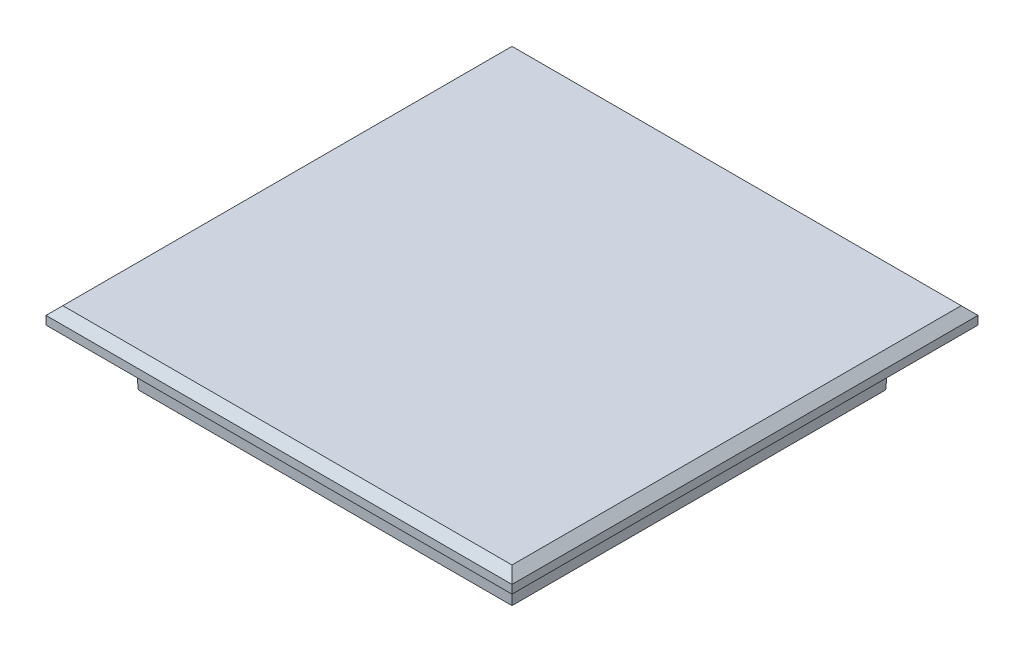
SolidWorks part; units mm, degrees
ref_plane "Front Plane" through (0, 0, 0) normal (0, 0, 1) x (1, 0, 0)
ref_plane "Top Plane" through (0, 0, 0) normal (0, 1, 0) x (1, 0, 0)
ref_plane "Right Plane" through (0, 0, 0) normal (1, 0, 0) x (0, 0, -1)
sketch "Sketch1" plane through (0, 0, 0) normal (0, 1, 0) x (1, 0, 0)
  line L0 (0, 43.1919) -> (0, -36.1744) construction
  line L1 (-68, 0) -> (63.8488, 0) construction
  line L3 (-34, -34) -> (34, -34) construction
  line L4 (-34, -34) -> (-34, 34) construction
  line L5 (-34, 34) -> (34, 34) construction
  line L6 (34, -34) -> (34, 34) construction
  line L7 (-34, -34) -> (34, 34) construction
  line L8 (-34, 34) -> (34, -34) construction
  line L12 (-33.8, 33.8) -> (33.8, 33.8)
  line L13 (33.8, -33.8) -> (33.8, 33.8)
  line L14 (-33.8, -33.8) -> (33.8, -33.8)
  line L15 (-33.8, -33.8) -> (-33.8, 33.8)
  line L16 (-30.8, 30.8) -> (30.8, 30.8)
  line L17 (30.8, -30.8) -> (30.8, 30.8)
  line L18 (-30.8, -30.8) -> (30.8, -30.8)
  line L19 (-30.8, -30.8) -> (-30.8, 30.8)
  point P5 (0, 0)
  dimension "D1" = 68
  dimension "D2" = 0.2
  dimension "D3" = 3
extrude "Boss-Extrude1" add sketch "Sketch1" against normal blind 10 draft 3
sketch "Sketch2" plane through (0, 0, 0) normal (0, 1, 0) x (1, 0, 0)
  line L1 (-41.5, -41.5) -> (41.5, -41.5)
  line L2 (-41.5, -41.5) -> (-41.5, 41.5)
  line L3 (-41.5, 41.5) -> (41.5, 41.5)
  line L4 (41.5, -41.5) -> (41.5, 41.5)
  line L5 (-41.5, -41.5) -> (41.5, 41.5) construction
  line L6 (-41.5, 41.5) -> (41.5, -41.5) construction
  point P0 (0, 0)
  dimension "D1" = 83
extrude "Boss-Extrude2" add sketch "Sketch2" along normal blind 3
chamfer "Chamfer1" distance 1.5 angle 45 4 edges at (0, 3, 41.5) (-41.5, 3, 0) (0, 3, -41.5) (41.5, 3, 0)
chamfer "Chamfer2" distance 2 angle 45 4 edges at (30.8, 0, 0) (0, 0, -30.8) (-30.8, 0, 0) (0, 0, 30.8)
